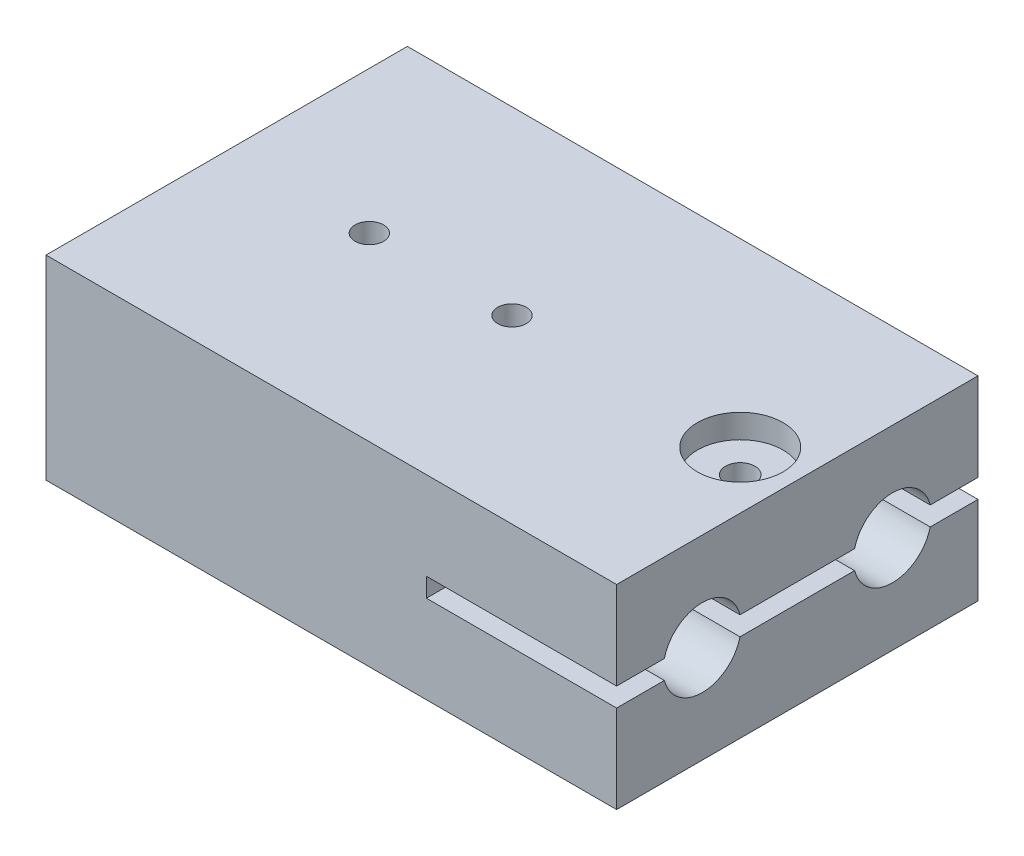
SolidWorks part; units mm, degrees
ref_plane "Alzado" through (0, 0, 0) normal (0, 0, 1) x (1, 0, 0)
ref_plane "Planta" through (0, 0, 0) normal (0, 1, 0) x (1, 0, 0)
ref_plane "Vista lateral" through (0, 0, 0) normal (1, 0, 0) x (0, 0, -1)
sketch "Croquis3" plane through (0, 0, 0) normal (1, 0, 0) x (0, 0, -1)
  line L1 (-19, -10.75) -> (19, -10.75)
  line L2 (-19, -10.75) -> (-19, 10.75)
  line L3 (-19, 10.75) -> (19, 10.75)
  line L4 (19, -10.75) -> (19, 10.75)
  line L5 (-19, -10.75) -> (19, 10.75) construction
  line L6 (-19, 10.75) -> (19, -10.75) construction
  point P0 (0, 0)
extrude "Saliente-Extruir2" add sketch "Croquis3" along normal blind 60
sketch "Croquis4" plane through (60, 0, 0) normal (1, 0, 0) x (0, 0, -1)
  line L0 (0, 0) -> (10, 0) construction
  line L1 (0, 0) -> (-10, 0) construction
  circle A0 centre (-10, 0) radius 4.1
  circle A1 centre (10, 0) radius 4.1
extrude "Cortar-Extruir2" cut sketch "Croquis4" against normal blind 60
sketch "Croquis5" plane through (0, 0, 19) normal (0, 0, 1) x (1, 0, 0)
  line L0 (60, 0) -> (40, 0) construction
  line L1 (60, 10.75) -> (60, -10.75) construction
  line L2 (40, 0) -> (40, 1) construction
  line L3 (40, 0) -> (40, -1) construction
  line L5 (40, 1) -> (60, 1)
  line L6 (40, 1) -> (40, -1)
  line L7 (40, -1) -> (60, -1)
  line L8 (60, 1) -> (60, -1)
extrude "Cortar-Extruir4" cut sketch "Croquis5" against normal blind 39
sketch "Croquis6" plane through (0, -10.75, 0) normal (0, -1, 0) x (1, 0, 0)
  line L0 (60, 0) -> (54, 0) construction
  line L1 (60, 19) -> (60, -19) construction
  line L2 (54, 0) -> (54, -14) construction
  line L3 (54, -14) -> (54, -19) construction
  line L4 (60, -19) -> (0, -19) construction
  line L5 (54, 0) -> (54, 14) construction
  line L6 (54, 14) -> (54, 19) construction
  line L7 (60, 19) -> (0, 19) construction
  circle A0 centre (54, 0) radius 3.5
extrude "Cortar-Extruir5" cut sketch "Croquis6" against normal blind 3
sketch "Croquis7" plane through (0, -10.75, 0) normal (0, -1, 0) x (1, 0, 0)
  circle A0 centre (54, 0) radius 1.55
extrude "Cortar-Extruir6" cut sketch "Croquis7" against normal blind 22
sketch "Croquis8" plane through (0, 10.75, 0) normal (0, 1, 0) x (1, 0, 0)
  circle A0 centre (54, 0) radius 4.5
extrude "Cortar-Extruir7" cut sketch "Croquis8" against normal blind 3
sketch "Croquis9" plane through (0, 10.75, 0) normal (0, 1, 0) x (1, 0, 0)
  line L0 (30, 0) -> (0, 0) construction
  line L3 (30, 0) -> (30, -14) construction
  line L4 (30, -14) -> (30, -19) construction
  line L5 (60, -19) -> (0, -19) construction
  line L6 (30, 0) -> (30, 14) construction
  line L7 (30, 14) -> (30, 19) construction
  line L8 (60, 19) -> (0, 19) construction
  line L9 (0, 19) -> (0, -19) construction
  line L10 (30, 0) -> (60, 0) construction
  line L11 (60, 19) -> (60, -19) construction
  circle A0 centre (30, 0) radius 1.5
  circle A1 centre (15, 0) radius 1.5
extrude "Cortar-Extruir8" cut sketch "Croquis9" against normal blind 15
sketch "Croquis10" plane through (0, 0, 0) normal (-1, 0, 0) x (0, 0, 1)
  line L0 (-19, 10.75) -> (-19, 10.25) construction
  line L1 (-19, -10.75) -> (-19, 10.75) construction
  line L2 (-19, -10.75) -> (-19, -10.25) construction
  line L4 (-19, 10.25) -> (19, 10.25)
  line L5 (-19, 10.25) -> (-19, 10.75)
  line L6 (-19, 10.75) -> (19, 10.75)
  line L7 (19, 10.25) -> (19, 10.75)
  line L8 (-19, -10.25) -> (19, -10.25)
  line L9 (-19, -10.25) -> (-19, -10.75)
  line L10 (-19, -10.75) -> (19, -10.75)
  line L11 (19, -10.25) -> (19, -10.75)
extrude "Cortar-Extruir9" cut sketch "Croquis10" against normal blind 60
